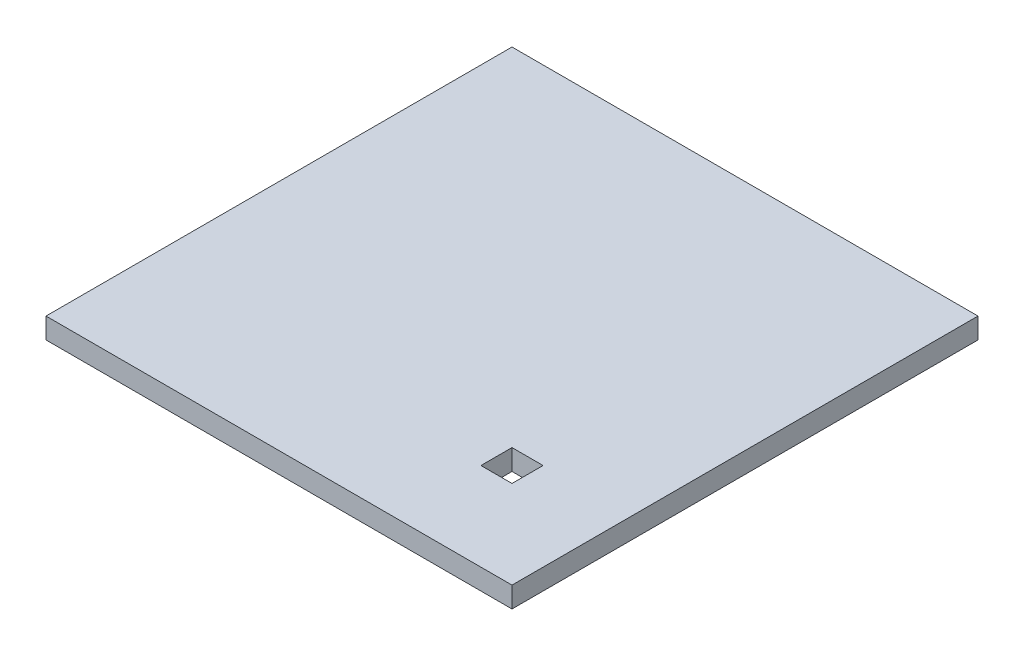
SolidWorks part; units mm, degrees
ref_plane "Alzado" through (0, 0, 0) normal (0, 0, 1) x (1, 0, 0)
ref_plane "Planta" through (0, 0, 0) normal (0, 1, 0) x (1, 0, 0)
ref_plane "Vista lateral" through (0, 0, 0) normal (1, 0, 0) x (0, 0, -1)
sketch "Croquis1" plane through (0, 0, 0) normal (0, 1, 0) x (1, 0, 0)
  line L1 (0, 0) -> (45, 0)
  line L2 (0, 0) -> (0, 45)
  line L3 (0, 45) -> (45, 45)
  line L4 (45, 0) -> (45, 45)
  dimension "D1" = 45
extrude "Saliente-Extruir1" add sketch "Croquis1" along normal blind 2
sketch "Croquis2" plane through (0, 2, 0) normal (0, 1, 0) x (1, 0, 0)
  line L0 (0, 0) -> (45, 45) construction
  line L2 (8.5, 8.5) -> (36.5, 8.5) construction
  line L3 (8.5, 8.5) -> (8.5, 36.5) construction
  line L4 (8.5, 36.5) -> (36.5, 36.5) construction
  line L5 (36.5, 8.5) -> (36.5, 36.5) construction
  line L6 (8.5, 8.5) -> (36.5, 36.5) construction
  line L7 (8.5, 36.5) -> (36.5, 8.5) construction
  line L8 (36.5, 8.5) -> (33.5, 8.5)
  line L9 (36.5, 8.5) -> (36.5, 11.5)
  line L10 (36.5, 11.5) -> (33.5, 11.5)
  line L11 (33.5, 8.5) -> (33.5, 11.5)
  point P4 (22.5, 22.5)
  dimension "D1" = 28
  dimension "D2" = 3
extrude "Cortar-Extruir1" cut sketch "Croquis2" against normal blind 5
